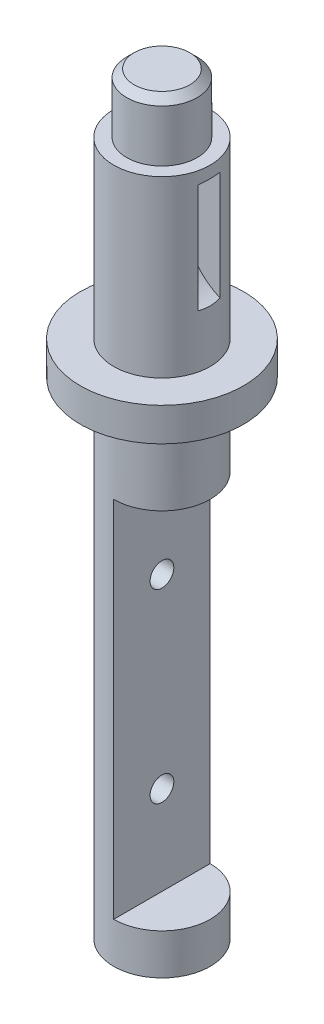
SolidWorks part; units mm, degrees
ref_plane "Front Plane" through (0, 0, 0) normal (0, 0, 1) x (1, 0, 0)
ref_plane "Top Plane" through (0, 0, 0) normal (0, 1, 0) x (1, 0, 0)
ref_plane "Right Plane" through (0, 0, 0) normal (1, 0, 0) x (0, 0, -1)
sketch "Sketch1" plane through (0, 0, 0) normal (0, 0, 1) x (1, 0, 0)
  line L0 (0, 0) -> (6.5, 0)
  line L1 (6.5, 0) -> (6.5, 65.5)
  line L2 (6.5, 65.5) -> (11, 65.5)
  line L3 (11, 65.5) -> (11, 70)
  line L4 (11, 70) -> (6.5, 70)
  line L5 (6.5, 70) -> (6.5, 93.5)
  line L6 (6.5, 93.5) -> (4.75, 93.5)
  line L7 (4.75, 93.5) -> (4.75, 101.5)
  line L8 (4.75, 101.5) -> (0, 101.5)
  line L9 (0, 101.5) -> (0, 0)
  line L10 (0, 101.5) -> (0, 0) construction
  point P8 (11, 67.75)
  point P12 (0, 50.75)
  dimension "D1" = 6.5
  dimension "D2" = 4.5
  dimension "D3" = 23.5
  dimension "D4" = 8
  dimension "D5" = 101.5
  dimension "D6" = 11
  dimension "D7" = 4.75
revolve "Revolve1" add sketch "Sketch1" angle 360 about L10
chamfer "Chamfer1" distance 1 angle 45 1 edges at (-4.75, 101.5, 0)
sketch "Sketch2" plane through (0, 0, 0) normal (0, 0, 1) x (1, 0, 0)
  line L0 (-6.5, 0) -> (6.5, 0) construction
  line L1 (-6.5, 65.5) -> (-6.5, 0) construction
  line L4 (0, 54.5) -> (13.6802, 54.5)
  line L5 (0, 54.5) -> (0, 5.5)
  line L6 (0, 5.5) -> (13.6802, 5.5)
  line L7 (13.6802, 54.5) -> (13.6802, 5.5)
  dimension "D1" = 49
  dimension "D2" = 5.5
  dimension "D3" = 6.5
extrude "Cut-Extrude2" cut sketch "Sketch2" against normal through all both and the other way through all
sketch "Sketch3" plane through (0, 0, 0) normal (0, 0, 1) x (1, 0, 0)
  line L0 (6.5, 70) -> (6.5, 93.5) construction
  line L1 (3.75, 101.5) -> (-3.75, 101.5) construction
  circle A0 centre (9.5, 84.5) radius 8
  point P2 (-41.0784, 78.2699)
  point P3 (1.5, 84.5)
  dimension "D1" = 16
  dimension "D2" = 5
  dimension "D3" = 17
sketch "Sketch6" plane through (0, 0, 0) normal (0, 0, 1) x (1, 0, 0)
extrude "Cut-Extrude3" cut sketch "Sketch3" against normal mid plane 3
sketch "Sketch7" plane through (0, 0, 0) normal (1, 0, 0) x (0, 0, -1)
  line L0 (-6.5, 0) -> (6.5, 0) construction
  circle A0 centre (0, 42.5) radius 1.6
  circle A1 centre (0, 17.5) radius 1.6
  dimension "D3" = 3.2
  dimension "D1" = 25
  dimension "D2" = 17.5
extrude "Cut-Extrude4" cut sketch "Sketch7" against normal through all both and the other way through all
